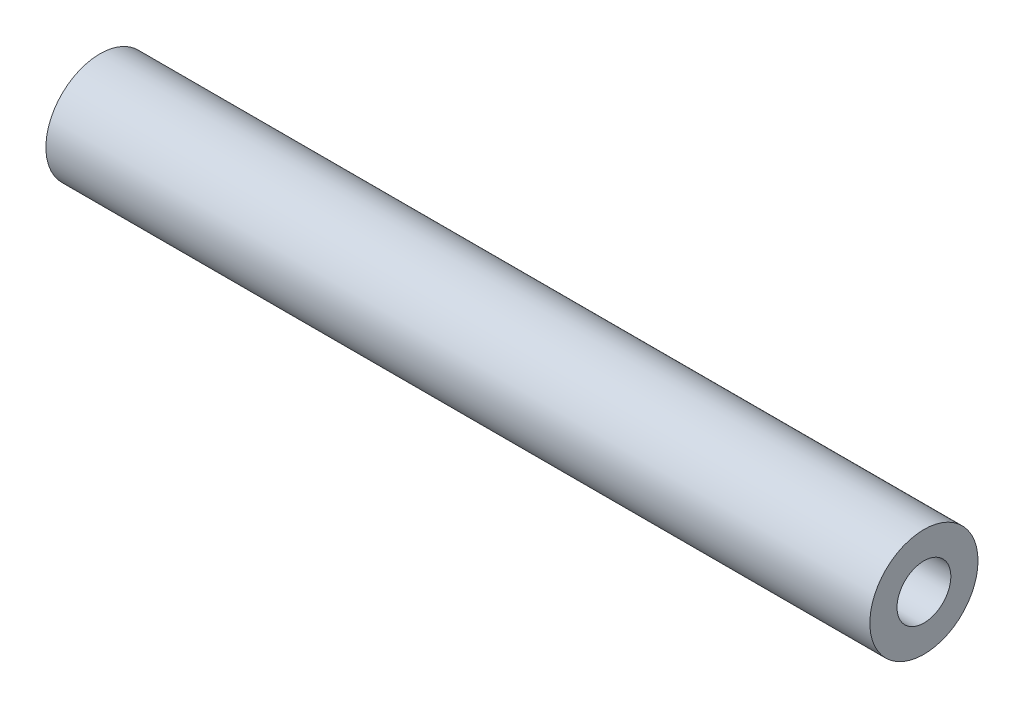
SolidWorks part; units mm, degrees
ref_plane "Piano frontale" through (0, 0, 0) normal (0, 0, 1) x (1, 0, 0)
ref_plane "Piano superiore" through (0, 0, 0) normal (0, 1, 0) x (1, 0, 0)
ref_plane "Piano destro" through (0, 0, 0) normal (1, 0, 0) x (0, 0, -1)
sketch "Schizzo2" plane through (0, 0, 0) normal (1, 0, 0) x (0, 0, -1)
  circle A0 centre (0, 0) radius 2.51
  circle A1 centre (0, 0) radius 1
  dimension "D1" = 5.02
  dimension "D2" = 2
extrude "Estrusione-Estrusione1" add sketch "Schizzo2" along normal mid plane 38.25
hole_wizard "Foro filettato M3x0.5-2" positions "Schizzo6" profile "Schizzo5" tap size "M3x0.5" standard "Ansi Metric"
sketch "Schizzo6" plane through (19.125, 0, 0) normal (1, 0, 0) x (0, 0, -1)
  point P0 (0, 0)
sketch "Schizzo5" plane through (19.125, 0, 0) normal (0, 1, 0) x (0, 0, -1)
  line L0 (0, 0) -> (0, 8.7511)
  line L1 (0, 8.7511) -> (1.25, 8)
  line L2 (1.25, 8) -> (1.25, 0)
  line L5 (1.25, 0) -> (0, 0)
  line L10 (0, 8.7511) -> (-1.25, 8) construction
  line L11 (0, -6.35) -> (0, 107.95) construction
  dimension "Tap Drill Dia." = 2.5
  dimension "Tap Drill Depth" = 8
  dimension "Drill Angle" = 118
mirror "Specchia1" about plane through (0, 0, 0) normal (1, 0, 0) of "Foro filettato M3x0.5-2"
